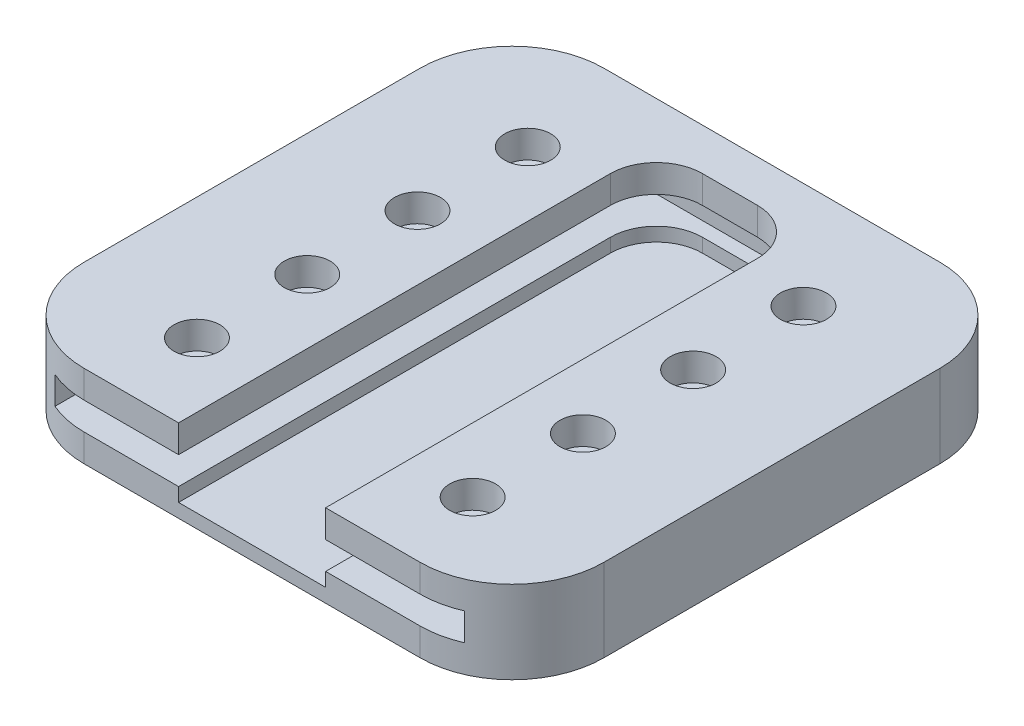
SolidWorks part; units mm, degrees
ref_plane "前视基准面" through (0, 0, 0) normal (0, 0, 1) x (1, 0, 0)
ref_plane "上视基准面" through (0, 0, 0) normal (0, 1, 0) x (1, 0, 0)
ref_plane "右视基准面" through (0, 0, 0) normal (1, 0, 0) x (0, 0, -1)
other "Configuration Table"
sketch "草图2" plane through (0, 0, 0) normal (0, 1, 0) x (1, 0, 0)
  line L0 (0, 0) -> (0, 29.1329) construction
  line L1 (28.2843, -18.2843) -> (28.2843, 18.2843)
  line L2 (18.2843, 28.2843) -> (-18.2843, 28.2843)
  line L3 (-28.2843, 18.2843) -> (-28.2843, -18.2843)
  line L4 (-18.2843, -28.2843) -> (18.2843, -28.2843)
  line L5 (0, 0) -> (28.2843, 0) construction
  circle A0 centre (0, 0) radius 28.2843 construction
  arc A1 (-28.2843, -18.2843) -> (-18.2843, -28.2843) centre (-18.2843, -18.2843) ccw
  arc A2 (28.2843, -18.2843) -> (18.2843, -28.2843) centre (18.2843, -18.2843) cw
  arc A3 (28.2843, 18.2843) -> (18.2843, 28.2843) centre (18.2843, 18.2843) ccw
  arc A4 (-18.2843, 28.2843) -> (-28.2843, 18.2843) centre (-18.2843, 18.2843) ccw
  dimension "D1" = 10
extrude "凸台-拉伸1" add sketch "草图2" along normal blind 3
sketch "草图3" plane through (0, 3, 0) normal (0, 1, 0) x (1, 0, 0)
  line L0 (0, 0) -> (28.2843, 0) construction
  line L1 (28.2843, -18.2843) -> (28.2843, 18.2843) construction
  line L2 (0, 0) -> (0, 28.2843) construction
  line L3 (18.2843, 28.2843) -> (-18.2843, 28.2843) construction
  circle A0 centre (12.7, 12.7) radius 3.18
  circle A1 centre (12.7, -12.7) radius 3.18
  circle A2 centre (-12.7, -12.7) radius 3.18
  circle A3 centre (-12.7, 12.7) radius 3.18
  dimension "D1" = 12.7
  dimension "D2" = 12.7
extrude "凸台-拉伸2" add sketch "草图3" against normal blind 8
sketch "草图5" plane through (0, 3, 0) normal (0, 1, 0) x (1, 0, 0)
  line L4 (-28.2843, 18.2843) -> (-28.2843, -18.2843) construction
  line L5 (-12.2843, 25.2843) -> (12.2843, 25.2843)
  line L6 (-22.2843, 15.2843) -> (-22.2843, -27.4494)
  line L8 (22.2843, 15.2843) -> (22.2843, -27.4494)
  line L9 (28.2843, -18.2843) -> (28.2843, 18.2843) construction
  line L10 (18.2843, 28.2843) -> (-18.2843, 28.2843) construction
  line L20 (18.2843, 28.2843) -> (-18.2843, 28.2843)
  line L21 (-28.2843, 18.2843) -> (-28.2843, -18.2843)
  line L22 (18.2843, 28.2843) -> (-18.2843, 28.2843)
  line L23 (-28.2843, 18.2843) -> (-28.2843, -18.2843)
  line L25 (28.2843, -18.2843) -> (28.2843, 18.2843)
  line L26 (28.2843, -18.2843) -> (28.2843, 18.2843)
  arc A0 (12.2843, 25.2843) -> (22.2843, 15.2843) centre (12.2843, 15.2843) cw
  arc A1 (-12.2843, 25.2843) -> (-22.2843, 15.2843) centre (-12.2843, 15.2843) ccw
  arc A14 (18.2843, -28.2843) -> (28.2843, -18.2843) centre (18.2843, -18.2843) ccw
  arc A15 (28.2843, 18.2843) -> (18.2843, 28.2843) centre (18.2843, 18.2843) ccw
  arc A16 (-28.2843, -18.2843) -> (-18.2843, -28.2843) centre (-18.2843, -18.2843) ccw
  arc A17 (-18.2843, 28.2843) -> (-28.2843, 18.2843) centre (-18.2843, 18.2843) ccw
  arc A18 (28.2843, 18.2843) -> (18.2843, 28.2843) centre (18.2843, 18.2843) ccw
  arc A19 (-28.2843, -18.2843) -> (-22.2843, -27.4494) centre (-18.2843, -18.2843) ccw
  arc A20 (-18.2843, 28.2843) -> (-28.2843, 18.2843) centre (-18.2843, 18.2843) ccw
  arc A21 (22.2843, -27.4494) -> (28.2843, -18.2843) centre (18.2843, -18.2843) ccw
  dimension "D6" = 10
  dimension "D1" = 6
  dimension "D2" = 6
  dimension "D3" = 3
  dimension "D4" = 0
  dimension "D5" = 0
extrude "凸台-拉伸3" add sketch "草图5" along normal blind 3
sketch "草图6" plane through (0, 6, 0) normal (0, 1, 0) x (1, 0, 0)
  line L2 (-28.2843, 18.2843) -> (-28.2843, -18.2843)
  line L3 (-28.2843, 18.2843) -> (-28.2843, -18.2843)
  line L24 (28.2843, -18.2843) -> (28.2843, 18.2843)
  line L25 (-18.2843, -28.2843) -> (18.2843, -28.2843)
  line L26 (18.2843, 28.2843) -> (-18.2843, 28.2843)
  line L27 (28.2843, -18.2843) -> (28.2843, 18.2843)
  line L28 (-18.2843, -28.2843) -> (18.2843, -28.2843)
  line L29 (18.2843, 28.2843) -> (-18.2843, 28.2843)
  arc A38 (28.2843, 18.2843) -> (18.2843, 28.2843) centre (18.2843, 18.2843) ccw
  arc A39 (22.2843, -27.4494) -> (28.2843, -18.2843) centre (18.2843, -18.2843) ccw
  arc A40 (18.2843, -28.2843) -> (22.2843, -27.4494) centre (18.2843, -18.2843) ccw
  arc A41 (-22.2843, -27.4494) -> (-18.2843, -28.2843) centre (-18.2843, -18.2843) ccw
  arc A42 (-28.2843, -18.2843) -> (-22.2843, -27.4494) centre (-18.2843, -18.2843) ccw
  arc A43 (-18.2843, 28.2843) -> (-28.2843, 18.2843) centre (-18.2843, 18.2843) ccw
  arc A44 (28.2843, 18.2843) -> (18.2843, 28.2843) centre (18.2843, 18.2843) ccw
  arc A45 (22.2843, -27.4494) -> (28.2843, -18.2843) centre (18.2843, -18.2843) ccw
  arc A46 (18.2843, -28.2843) -> (22.2843, -27.4494) centre (18.2843, -18.2843) ccw
  arc A47 (-22.2843, -27.4494) -> (-18.2843, -28.2843) centre (-18.2843, -18.2843) ccw
  arc A48 (-28.2843, -18.2843) -> (-22.2843, -27.4494) centre (-18.2843, -18.2843) ccw
  arc A49 (-18.2843, 28.2843) -> (-28.2843, 18.2843) centre (-18.2843, 18.2843) ccw
  dimension "D1" = 0
  dimension "D2" = 0
extrude "凸台-拉伸4" add sketch "草图6" along normal blind 3
sketch "草图7" plane through (0, 9, 0) normal (0, 1, 0) x (1, 0, 0)
  line L0 (-18.2843, -28.2843) -> (18.2843, -28.2843) construction
  line L1 (-8, -28.2843) -> (8, -28.2843)
  line L2 (-8, -28.2843) -> (-8, 18.7157)
  line L3 (-3, 23.7157) -> (3, 23.7157)
  line L4 (8, -28.2843) -> (8, 18.7157)
  line L5 (0, -28.2843) -> (0, 14.343) construction
  arc A0 (-8, 18.7157) -> (-3, 23.7157) centre (-3, 18.7157) cw
  arc A1 (3, 23.7157) -> (8, 18.7157) centre (3, 18.7157) cw
  circle A2 centre (-15, 16.7157) radius 2.5
  circle A3 centre (-15, 4.7157) radius 2.5
  circle A4 centre (-15, -7.2843) radius 2.5
  circle A5 centre (-15, -19.2843) radius 2.5
  circle A6 centre (15, -19.2843) radius 2.5
  circle A7 centre (15, -7.2843) radius 2.5
  circle A8 centre (15, 4.7157) radius 2.5
  circle A9 centre (15, 16.7157) radius 2.5
  point P9 (-8, 23.7157)
  dimension "D4" = 5
  dimension "D5" = 7
  dimension "D1" = 8
  dimension "D2" = 8
  dimension "D3" = 52
  dimension "D6" = 15
  dimension "D7" = 4
extrude "切除-拉伸1" cut sketch "草图7" against normal blind 7.5
